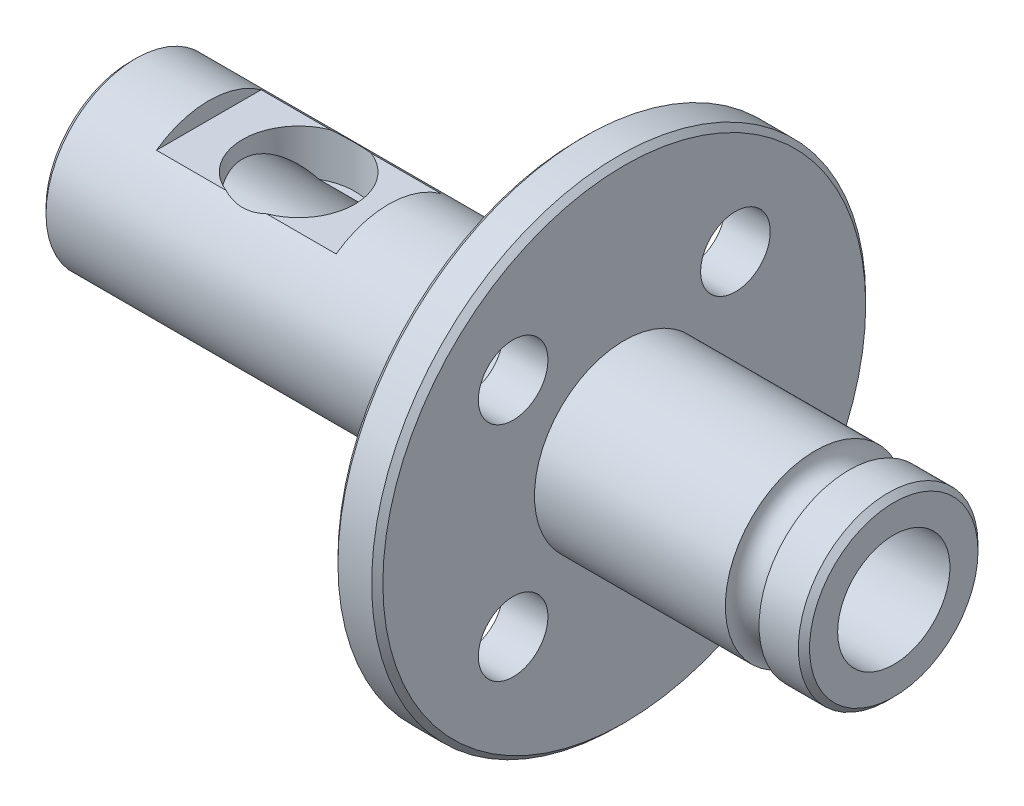
SolidWorks part; units mm, degrees
ref_plane "Front Plane" through (0, 0, 0) normal (0, 0, 1) x (1, 0, 0)
ref_plane "Top Plane" through (0, 0, 0) normal (0, 1, 0) x (1, 0, 0)
ref_plane "Right Plane" through (0, 0, 0) normal (1, 0, 0) x (0, 0, -1)
sketch "Sketch1" plane through (0, 0, 0) normal (0, 0, 1) x (1, 0, 0)
  line L0 (0, 0) -> (0, 4)
  line L1 (0, 4) -> (20, 4)
  line L2 (20, 4) -> (20, 11)
  line L3 (20, 11) -> (22, 11)
  line L4 (22, 11) -> (22, 4)
  line L5 (22, 4) -> (30.5, 4)
  line L6 (34, 4) -> (34, 0)
  line L7 (34, 0) -> (0, 0)
  line L8 (32, 4) -> (34, 4)
  arc A0 (30.5, 4) -> (32, 4) centre (31.25, 4) ccw
  dimension "D7" = 1.5
  dimension "D1" = 34
  dimension "D2" = 7
  dimension "D3" = 7
  dimension "D4" = 2
  dimension "D5" = 20
  dimension "D6" = 4
  dimension "D8" = 2.75
revolve "Revolve1" add sketch "Sketch1" angle 360 about L7
sketch "Sketch2" plane through (20, 0, 0) normal (-1, 0, 0) x (0, 0, 1)
  line L0 (0, 0) -> (0, 7) construction
  line L1 (0, 0) -> (4.9497, 4.9497) construction
  line L2 (-7, 0) -> (7, 0) construction
  circle A0 centre (0, 0) radius 7 construction
  circle A1 centre (4.9497, 4.9497) radius 1.55
  circle A2 centre (-4.9497, 4.9497) radius 1.55
  circle A3 centre (4.9497, -4.9497) radius 1.55
  circle A4 centre (-4.9497, -4.9497) radius 1.55
  dimension "D1" = 14
  dimension "D3" = 3.1
  dimension "D2" = 45
extrude "Cut-Extrude1" cut sketch "Sketch2" against normal through all
sketch "Sketch3" plane through (0, 0, 0) normal (-1, 0, 0) x (0, 0, 1)
  circle A0 centre (0, 0) radius 2.5
  dimension "D1" = 5
extrude "Cut-Extrude2" cut sketch "Sketch3" against normal through all
ref_plane "Plane1" through (0, 4, 0) normal (0, 1, 0) x (1, 0, 0)
sketch "Sketch4" plane through (0, 4, 0) normal (0, 1, 0) x (1, 0, 0)
  line L1 (3.5, -2.5) -> (11.5, -2.5)
  line L2 (3.5, -2.5) -> (3.5, 2.5)
  line L3 (3.5, 2.5) -> (11.5, 2.5)
  line L4 (11.5, -2.5) -> (11.5, 2.5)
  line L5 (3.5, -2.5) -> (11.5, 2.5) construction
  line L6 (3.5, 2.5) -> (11.5, -2.5) construction
  point P0 (7.5, 0)
  dimension "D1" = 8
  dimension "D2" = 7.5
  dimension "D3" = 5
extrude "Cut-Extrude3" cut sketch "Sketch4" against normal blind 0.75
sketch "Sketch5" plane through (0, 3.25, 0) normal (0, 1, 0) x (1, 0, 0)
  circle A0 centre (7.5, 0) radius 2.5
  dimension "D1" = 5
  dimension "D2" = 7.5
extrude "Cut-Extrude4" cut sketch "Sketch5" against normal blind 2
chamfer "Chamfer1" distance 0.25 angle 45 4 edges at (34, 0, -4) (22, 0, -11) (20, 0, -11) (0, 0, -4)
